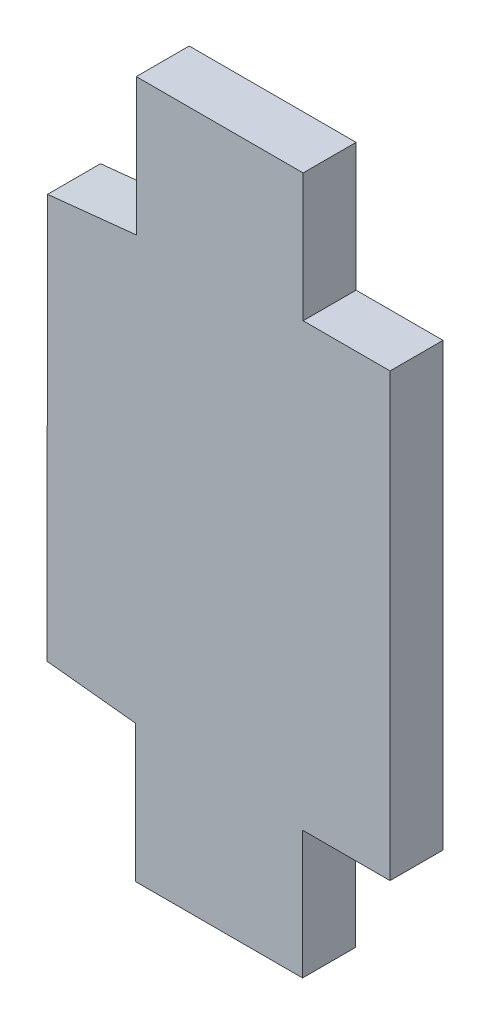
SolidWorks part; units mm, degrees
ref_plane "Front" through (0, 0, 0) normal (0, 0, 1) x (1, 0, 0)
ref_plane "Top" through (0, 0, 0) normal (0, 1, 0) x (1, 0, 0)
ref_plane "Right" through (0, 0, 0) normal (1, 0, 0) x (0, 0, -1)
sketch "Sketch1" plane through (0, 0, 0) normal (0, 0, 1) x (1, 0, 0)
  line L0 (668.9565, -27.0446) -> (668.9565, -2.0446)
  line L1 (649.5576, -3.081) -> (649.5272, -25.9967)
  line L4 (664.0018, -34.2964) -> (654.5518, -34.2964)
  line L5 (654.5518, -26.5315) -> (649.5272, -25.9967)
  line L6 (654.5518, -26.5315) -> (654.5518, -34.2964)
  line L7 (668.9565, -27.0446) -> (664.0018, -27.0446)
  line L8 (664.0018, -27.0446) -> (664.0018, -34.2964)
  line L9 (664.0337, 5.2054) -> (654.5837, 5.2054)
  line L10 (654.5837, -2.5595) -> (649.5576, -3.081)
  line L11 (654.5837, -2.5595) -> (654.5837, 5.2054)
  line L12 (664.0337, -2.0446) -> (664.0337, 5.2054)
  line L13 (668.9565, -2.0446) -> (664.0337, -2.0446)
  dimension "D1" = 7.25
  dimension "D2" = 7.2518
  dimension "D3" = 7.7649
  dimension "D4" = 96
  dimension "D5" = 9.45
  dimension "D6" = 96
  dimension "D7" = 90
  dimension "D8" = 90
  dimension "D9" = 9.45
  dimension "D10" = 25
extrude "Base-Extrude" add sketch "Sketch1" along normal blind 3
